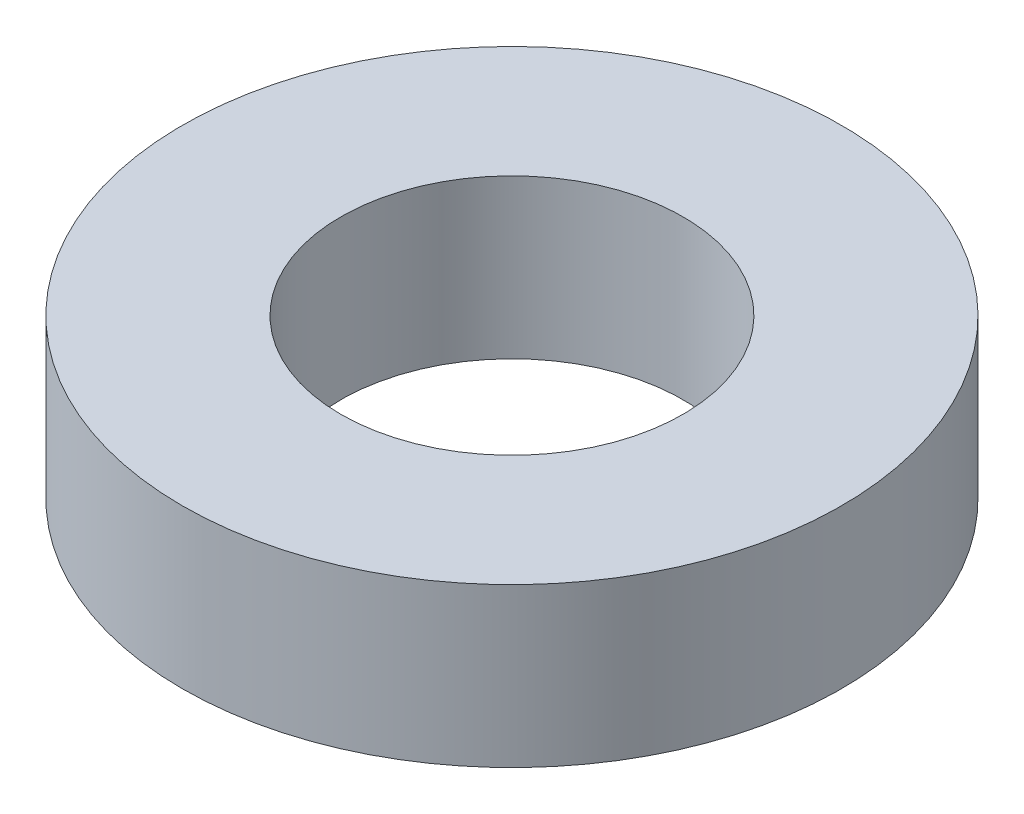
SolidWorks part; units mm, degrees
ref_plane "Front Plane" through (0, 0, 0) normal (0, 0, 1) x (1, 0, 0)
ref_plane "Top Plane" through (0, 0, 0) normal (0, 1, 0) x (1, 0, 0)
ref_plane "Right Plane" through (0, 0, 0) normal (1, 0, 0) x (0, 0, -1)
sketch "Sketch1" plane through (0, 0, 0) normal (0, 1, 0) x (1, 0, 0)
  circle A0 centre (0, 0) radius 3.429
  circle A1 centre (0, 0) radius 6.604
  dimension "D1" = 3.175
  dimension "D2" = 6.858
extrude "Boss-Extrude1" add sketch "Sketch1" along normal blind 3.175
